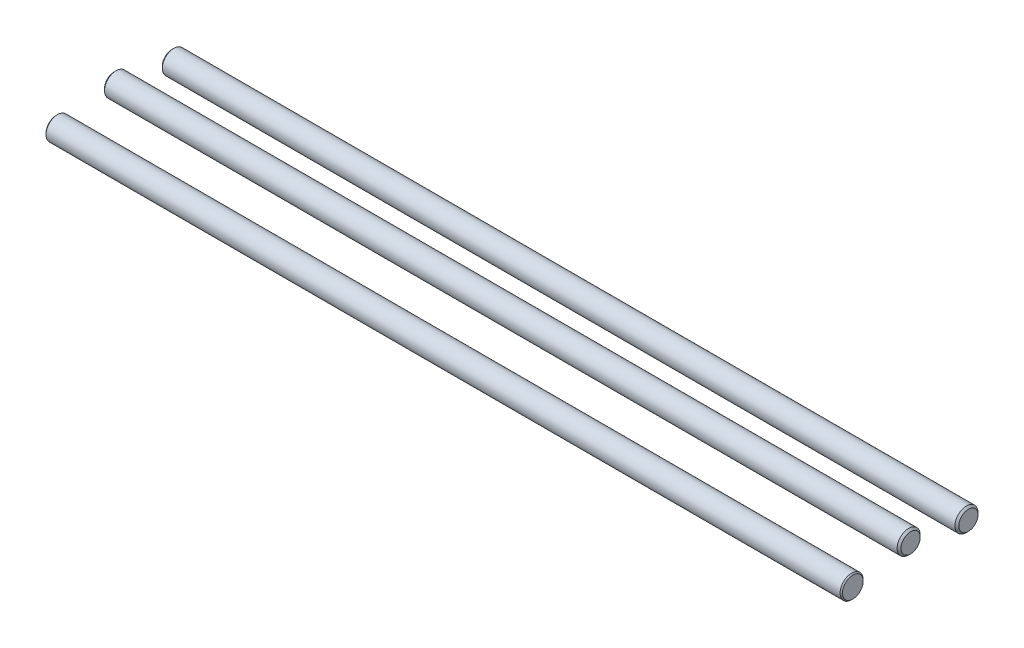
SolidWorks part; units mm, degrees
material "5052-H32"
ref_plane "Front Plane" through (0, 0, 0) normal (0, 0, 1) x (1, 0, 0)
ref_plane "Top Plane" through (0, 0, 0) normal (0, 1, 0) x (1, 0, 0)
ref_plane "Right Plane" through (0, 0, 0) normal (1, 0, 0) x (0, 0, -1)
sketch "Sketch2" plane through (0, 0, 0) normal (1, 0, 0) x (0, 0, -1)
  circle A0 centre (15, -2.4579) radius 3 construction
  circle A1 centre (-15, -2.4579) radius 3 construction
  circle A2 centre (0, 0) radius 3 construction
  circle A3 centre (15, -2.4579) radius 3
  circle A4 centre (-15, -2.4579) radius 3
  circle A5 centre (0, 0) radius 3
extrude "Boss-Extrude1" add sketch "Sketch2" against normal up to vertex (140.1 mm away) from vertex at -36.7
chamfer "Chamfer1" distance 0.3 angle 45 1 edges at (-36.7, -2.4579, 12)
chamfer "Chamfer2" distance 0.5 angle 45 1 edges at (-36.7, 0, -3)
chamfer "Chamfer3" distance 0.5 angle 45 1 edges at (-36.7, -2.4579, -18)
mirror "Mirror9" about plane through (-140.1, 0, 0) normal (1, 0, 0) of bodies 103 102 101
